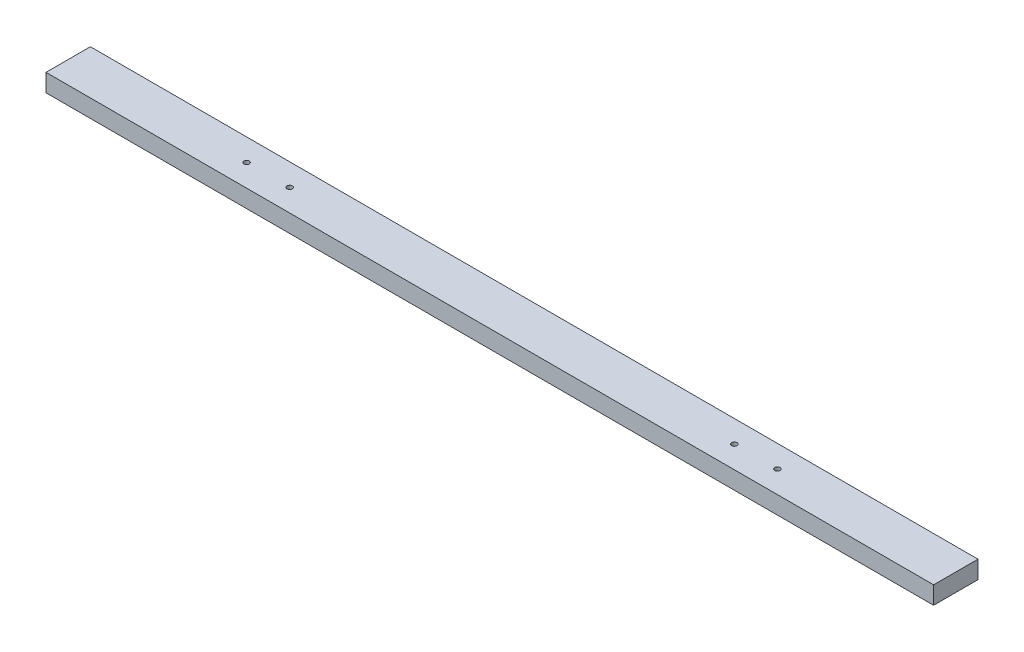
SolidWorks part; units mm, degrees
ref_plane "前视基准面" through (0, 0, 0) normal (0, 0, 1) x (1, 0, 0)
ref_plane "上视基准面" through (0, 0, 0) normal (0, 1, 0) x (1, 0, 0)
ref_plane "右视基准面" through (0, 0, 0) normal (1, 0, 0) x (0, 0, -1)
other "Configuration Table"
sketch "草图1" plane through (0, 0, 0) normal (0, 1, 0) x (1, 0, 0)
  line L0 (500, 50) -> (500, 0) construction
  line L1 (0, 0) -> (1000, 0)
  line L2 (0, 0) -> (0, 50)
  line L3 (0, 50) -> (1000, 50)
  line L4 (1000, 0) -> (1000, 50)
  circle A0 centre (799, 25) radius 3
  circle A1 centre (750.5, 25) radius 3
  circle A2 centre (201, 25) radius 3
  circle A3 centre (249.5, 25) radius 3
  point P9 (500, 50)
  point P16 (1000, 25)
  dimension "D3" = 6
  dimension "D5" = 6
  dimension "D1" = 1000
  dimension "D2" = 50
  dimension "D4" = 48.5
  dimension "D6" = 250.5
  dimension "D7" = 0
  dimension "D8" = 0
extrude "凸台-拉伸1" add sketch "草图1" along normal blind 20
equation "\"D6@草图1\"=(297+204)/2"
